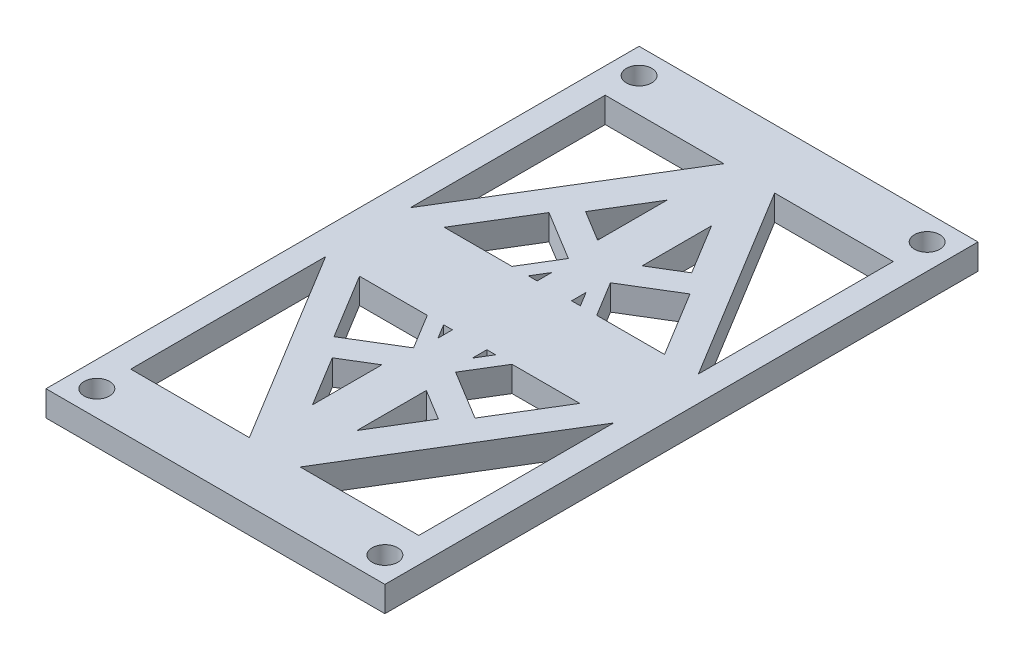
SolidWorks part; units mm, degrees
ref_plane "前视基准面" through (0, 0, 0) normal (0, 0, 1) x (1, 0, 0)
ref_plane "上视基准面" through (0, 0, 0) normal (0, 1, 0) x (1, 0, 0)
ref_plane "右视基准面" through (0, 0, 0) normal (1, 0, 0) x (0, 0, -1)
other "Configuration Table"
sketch "草图1" plane through (0, 0, 0) normal (0, 1, 0) x (1, 0, 0)
  line L1 (20, 35) -> (-20, 35)
  line L2 (20, 35) -> (20, -35)
  line L3 (20, -35) -> (-20, -35)
  line L4 (-20, 35) -> (-20, -35)
  line L5 (20, 35) -> (-20, -35) construction
  line L6 (20, -35) -> (-20, 35) construction
  point P0 (0, 0)
  dimension "D1" = 40
  dimension "D2" = 70
extrude "凸台-拉伸1" add sketch "草图1" along normal blind 3
sketch "草图2" plane through (0, 3, 0) normal (0, 1, 0) x (1, 0, 0)
  line L4 (-20, 35) -> (-20, -35)
  line L5 (-20, -35) -> (20, -35)
  line L6 (20, -35) -> (20, 35)
  line L7 (20, 35) -> (-20, 35)
  line L8 (-20, 35) -> (-20, -35)
  line L9 (-20, -35) -> (20, -35)
  line L10 (20, -35) -> (20, 35)
  line L11 (20, 35) -> (-20, 35)
  circle A0 centre (-17, -32) radius 1.5
  circle A1 centre (17, -32) radius 1.5
  circle A2 centre (17, 32) radius 1.5
  circle A3 centre (-17, 32) radius 1.5
  point P12 (0, 0)
  point P14 (20, -32.3186)
  point P15 (22.4634, -33.0391)
  dimension "D2" = 3
  dimension "D3" = 3
  dimension "D4" = 3
  dimension "D5" = 3
  dimension "D6" = 3
  dimension "D7" = 3
  dimension "D8" = 3
  dimension "D9" = 3
  dimension "D10" = 3
  dimension "D11" = 3
  dimension "D12" = 3
  dimension "D13" = 3
  dimension "D1" = 0
extrude "切除-拉伸1" cut sketch "草图2" against normal blind 3 contours A3 | A0 | A2 | A1
chamfer "倒角1" distance 0.5 angle 45 4 edges at (17, 0, -30.5) (-17, 0, -30.5) (-17, 0, 33.5) (17, 0, 33.5)
sketch "草图3" plane through (0, 3, 0) normal (0, 1, 0) x (1, 0, 0)
  line L0 (0, 55.591) -> (0, -48.6788) construction
  line L1 (-50.9568, 0) -> (48.0727, 0) construction
  line L2 (-17, 28) -> (-17, 5)
  line L3 (-17, 5) -> (-3, 28)
  line L4 (-20, 35) -> (-20, -35)
  line L5 (-20, -35) -> (20, -35)
  line L6 (20, -35) -> (20, 35)
  line L7 (20, 35) -> (-20, 35)
  line L8 (-20, 35) -> (-20, -35)
  line L9 (-20, -35) -> (20, -35)
  line L10 (20, -35) -> (20, 35)
  line L11 (20, 35) -> (-20, 35)
  line L12 (-3, 28) -> (-17, 28)
  line L13 (-2.6228, 20.9265) -> (-6.2625, 14.9471)
  line L14 (-6.2625, 14.9471) -> (-2.6228, 12.7317)
  line L15 (-2.6228, 12.7317) -> (-2.6228, 20.9265)
  line L16 (-8.3205, 12.6878) -> (-2.4832, 9.1347)
  line L17 (-2.4832, 9.1347) -> (-5, 5)
  line L18 (-5, 5) -> (-13, 5)
  line L19 (-13, 5) -> (-8.3205, 12.6878)
  line L20 (-2.0328, 6.7084) -> (-3.0727, 5)
  line L21 (-3.0727, 5) -> (-2.0328, 5)
  line L22 (-2.0328, 5) -> (-2.0328, 6.7084)
  line L23 (3.0727, 5) -> (2.0328, 5)
  line L24 (2.0328, 6.7084) -> (3.0727, 5)
  line L25 (2.0328, 5) -> (2.0328, 6.7084)
  line L26 (5, 5) -> (13, 5)
  line L27 (2.4832, 9.1347) -> (5, 5)
  line L28 (8.3205, 12.6878) -> (2.4832, 9.1347)
  line L29 (13, 5) -> (8.3205, 12.6878)
  line L30 (6.2625, 14.9471) -> (2.6228, 12.7317)
  line L31 (2.6228, 20.9265) -> (6.2625, 14.9471)
  line L32 (2.6228, 12.7317) -> (2.6228, 20.9265)
  line L33 (17, 5) -> (3, 28)
  line L34 (17, 28) -> (17, 5)
  line L35 (3, 28) -> (17, 28)
  line L36 (2.0328, -6.7084) -> (3.0727, -5)
  line L37 (2.0328, -5) -> (2.0328, -6.7084)
  line L38 (3.0727, -5) -> (2.0328, -5)
  line L39 (-3.0727, -5) -> (-2.0328, -5)
  line L40 (-2.0328, -6.7084) -> (-3.0727, -5)
  line L41 (-2.0328, -5) -> (-2.0328, -6.7084)
  line L42 (2.4832, -9.1347) -> (5, -5)
  line L43 (8.3205, -12.6878) -> (2.4832, -9.1347)
  line L44 (13, -5) -> (8.3205, -12.6878)
  line L45 (5, -5) -> (13, -5)
  line L46 (-5, -5) -> (-13, -5)
  line L47 (-2.4832, -9.1347) -> (-5, -5)
  line L48 (-8.3205, -12.6878) -> (-2.4832, -9.1347)
  line L49 (-13, -5) -> (-8.3205, -12.6878)
  line L50 (-6.2625, -14.9471) -> (-2.6228, -12.7317)
  line L51 (-2.6228, -20.9265) -> (-6.2625, -14.9471)
  line L52 (-2.6228, -12.7317) -> (-2.6228, -20.9265)
  line L53 (2.6228, -20.9265) -> (6.2625, -14.9471)
  line L54 (2.6228, -12.7317) -> (2.6228, -20.9265)
  line L55 (6.2625, -14.9471) -> (2.6228, -12.7317)
  line L56 (17, -28) -> (17, -5)
  line L57 (3, -28) -> (17, -28)
  line L58 (17, -5) -> (3, -28)
  line L59 (-17, -5) -> (-3, -28)
  line L60 (-17, -28) -> (-17, -5)
  line L61 (-3, -28) -> (-17, -28)
  dimension "D2" = 23
  dimension "D3" = 14
  dimension "D4" = 4
  dimension "D5" = 4
  dimension "D6" = 9
  dimension "D7" = 7
  dimension "D8" = 8
  dimension "D9" = 3
  dimension "D10" = 7
  dimension "D11" = 3
  dimension "D12" = 2
  dimension "D13" = 1.6463
  dimension "D1" = 0
extrude "切除-拉伸2" cut sketch "草图3" against normal blind 3 contours L33 L35 L34 | L12 L2 L3 | L59 L61 L60 | L56 L58 L57 | L42 L45 L44 L43 | L53 L55 L54 | L50 L52 L51 | L46 L49 L48 L47 | L39 L41 L40 | L36 L38 L37 | L26 L29 L28 L27 | L30 L32 L31 | L15 L13 L14 | L19 L16 L17 L18 | L22 L20 L21 | L23 L25 L24
